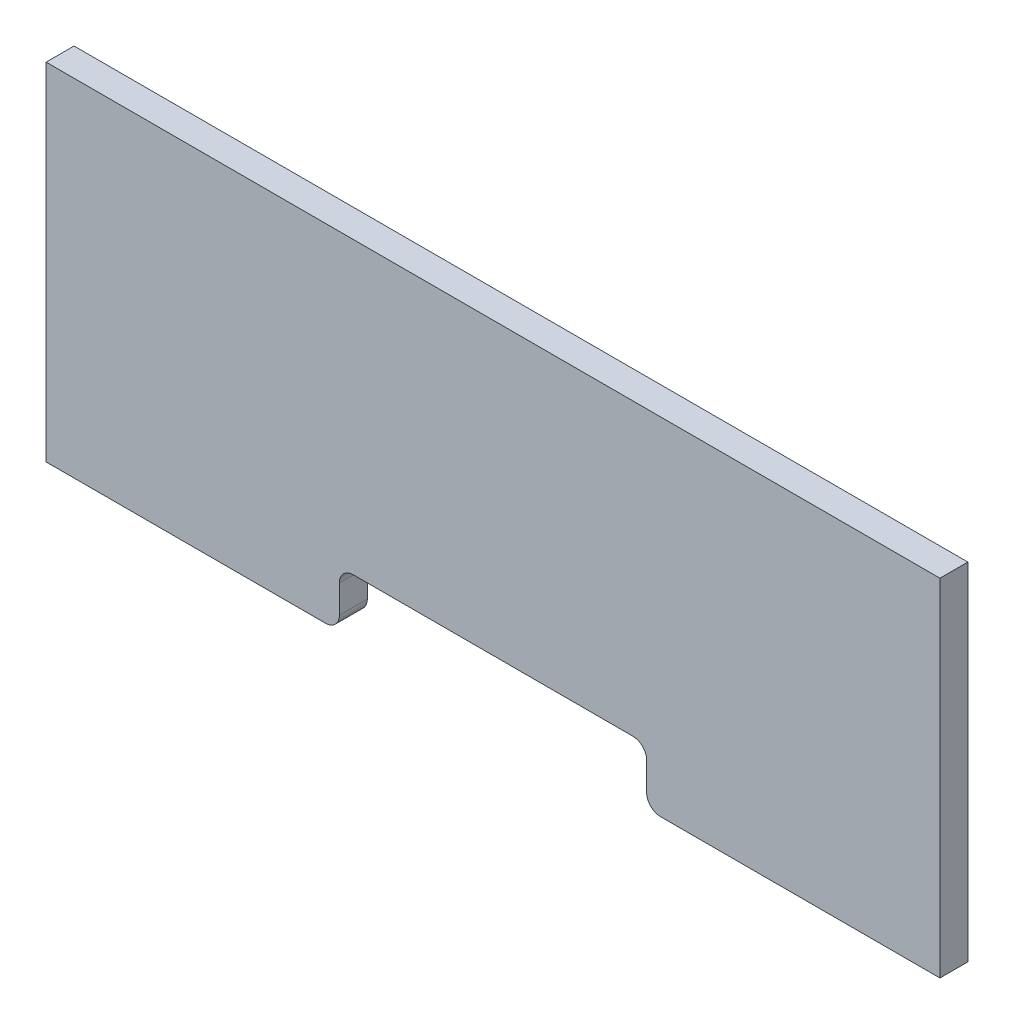
SolidWorks part; units mm, degrees
material "Copper"
ref_plane "Front Plane" through (0, 0, 0) normal (0, 0, 1) x (1, 0, 0)
ref_plane "Top Plane" through (0, 0, 0) normal (0, 1, 0) x (1, 0, 0)
ref_plane "Right Plane" through (0, 0, 0) normal (1, 0, 0) x (0, 0, -1)
sketch "Sketch1" plane through (0, 0, 0) normal (0, 0, 1) x (1, 0, 0)
  line L1 (0, 0) -> (203.2, 0)
  line L2 (0, 0) -> (0, 78.7146)
  line L3 (0, 78.7146) -> (203.2, 78.7146)
  line L4 (203.2, 0) -> (203.2, 78.7146)
  dimension "D1" = 203.2
  dimension "D2" = 78.7146
extrude "Boss-Extrude1" add sketch "Sketch1" along normal blind 6.35
sketch "Sketch2" plane through (0, 0, 6.35) normal (0, 0, 1) x (1, 0, 0)
  line L0 (0, 0) -> (203.2, 0) construction
  line L1 (66.675, 0) -> (136.525, 0)
  line L2 (66.675, 0) -> (66.675, 12.7)
  line L3 (66.675, 12.7) -> (136.525, 12.7)
  line L4 (136.525, 0) -> (136.525, 12.7)
  line L5 (101.6, 78.7146) -> (101.6, 12.7) construction
  line L6 (203.2, 78.7146) -> (0, 78.7146) construction
  dimension "D1" = 69.85
  dimension "D2" = 12.7
extrude "Cut-Extrude1" cut sketch "Sketch2" against normal through all
fillet "Fillet1" radius 3.175 4 edges at (136.525, 0, 3.175) (136.525, 12.7, 3.175) (66.675, 12.7, 3.175) (66.675, 0, 3.175)
